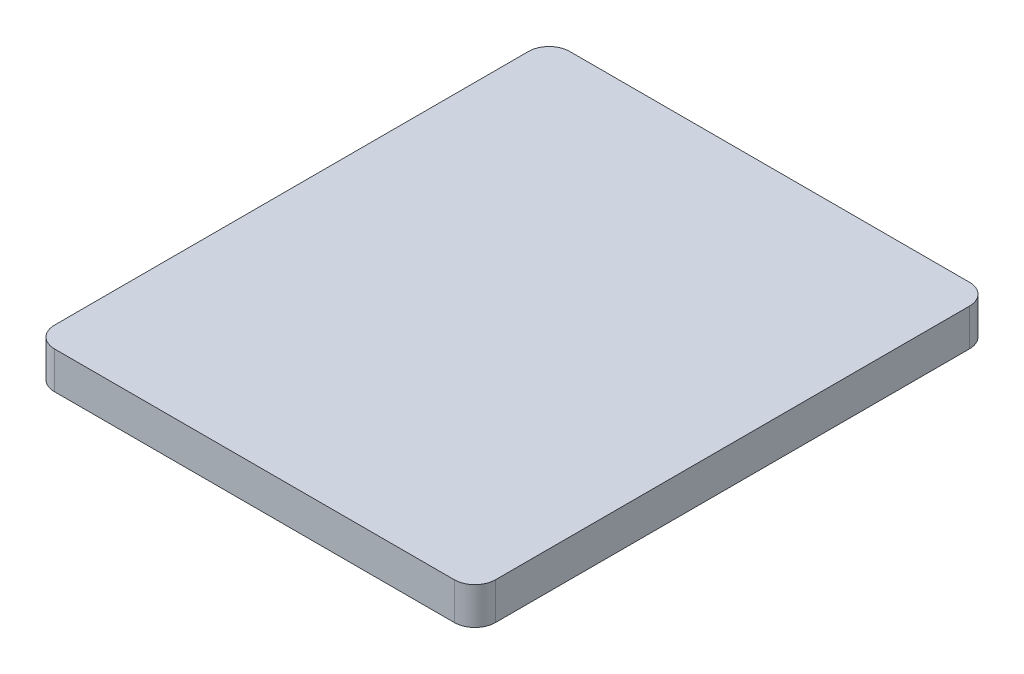
SolidWorks part; units mm, degrees
ref_plane "前视基准面" through (0, 0, 0) normal (0, 0, 1) x (1, 0, 0)
ref_plane "上视基准面" through (0, 0, 0) normal (0, 1, 0) x (1, 0, 0)
ref_plane "右视基准面" through (0, 0, 0) normal (1, 0, 0) x (0, 0, -1)
other "Configuration Table"
sketch "草图1" plane through (0, 0, 0) normal (0, 1, 0) x (1, 0, 0)
  line L1 (-107, -125) -> (107, -125)
  line L2 (-107, -125) -> (-107, 125)
  line L3 (-107, 125) -> (107, 125)
  line L4 (107, -125) -> (107, 125)
  point P4 (-107, 0)
  point P6 (0, 125)
  dimension "D1" = 250
  dimension "D2" = 214
extrude "凸台-拉伸1" add sketch "草图1" along normal blind 18
fillet "圆角1" radius 10 4 edges at (-107, 9, -125) (107, 9, -125) (107, 9, 125) (-107, 9, 125)
